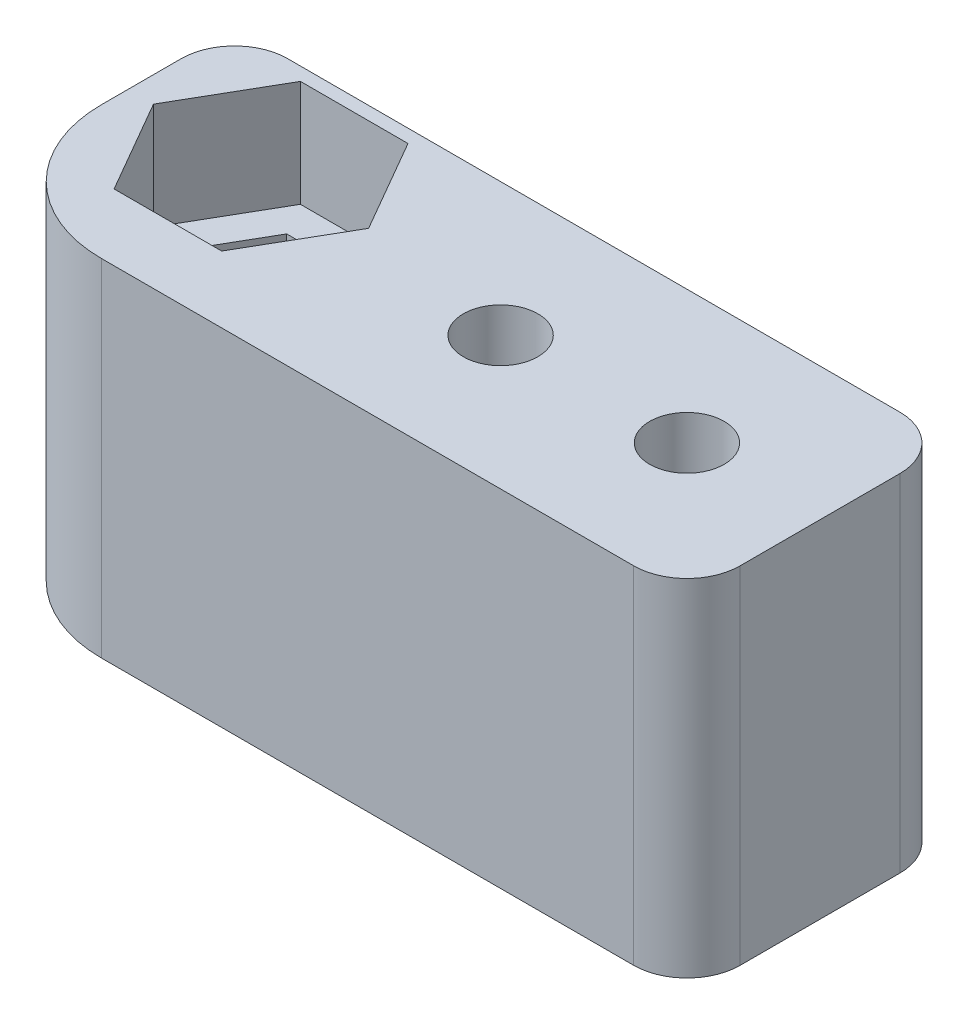
SolidWorks part; units mm, degrees
ref_plane "Front Plane" through (0, 0, 0) normal (0, 0, 1) x (1, 0, 0)
ref_plane "Top Plane" through (0, 0, 0) normal (0, 1, 0) x (1, 0, 0)
ref_plane "Right Plane" through (0, 0, 0) normal (1, 0, 0) x (0, 0, -1)
sketch "Sketch1" plane through (0, 0, 0) normal (0, 1, 0) x (1, 0, 0)
  line L1 (-19.05, 6.35) -> (15.24, 6.35)
  line L2 (-19.05, 6.35) -> (-19.05, -6.35)
  line L3 (-19.05, -6.35) -> (15.24, -6.35)
  line L4 (15.24, 6.35) -> (15.24, -6.35)
  circle A0 centre (-12.7, 1.27) radius 2.286
  circle A1 centre (0, 0) radius 1.778
  circle A2 centre (8.89, 0) radius 1.778
  dimension "D7" = 4.572
  dimension "D8" = 3.556
  dimension "D1" = 8.89
  dimension "D2" = 5.08
  dimension "D3" = 12.7
  dimension "D4" = 6.35
  dimension "D5" = 12.7
  dimension "D6" = 6.35
  dimension "D9" = 6.35
extrude "Boss-Extrude1" add sketch "Sketch1" along normal blind 16.51
fillet "Fillet1" radius 2.54 3 edges at (-19.05, 8.255, -6.35) (15.24, 8.255, -6.35) (15.24, 8.255, 6.35)
fillet "Fillet2" radius 6.35 1 edges at (-19.05, 8.255, 6.35)
sketch "Sketch4" plane through (0, 16.51, 0) normal (0, 1, 0) x (1, 0, 0)
  line L1 (-7.5674, 1.27) -> (-10.1337, 5.715)
  line L2 (-10.1337, 5.715) -> (-15.2663, 5.715)
  line L3 (-15.2663, 5.715) -> (-17.8326, 1.27)
  line L4 (-17.8326, 1.27) -> (-15.2663, -3.175)
  line L5 (-15.2663, -3.175) -> (-10.1337, -3.175)
  line L6 (-10.1337, -3.175) -> (-7.5674, 1.27)
  circle A0 centre (-12.7, 1.27) radius 4.445 construction
  dimension "D1" = 8.89
extrude "Cut-Extrude2" cut sketch "Sketch4" against normal blind 5.08
sketch "Sketch5" plane through (0, 11.43, 0) normal (0, 1, 0) x (1, 0, 0)
  line L1 (-9.3564, 1.27) -> (-11.0282, 4.1656)
  line L2 (-11.0282, 4.1656) -> (-14.3718, 4.1656)
  line L3 (-14.3718, 4.1656) -> (-16.0436, 1.27)
  line L4 (-16.0436, 1.27) -> (-14.3718, -1.6256)
  line L5 (-14.3718, -1.6256) -> (-11.0282, -1.6256)
  line L6 (-11.0282, -1.6256) -> (-9.3564, 1.27)
  circle A0 centre (-12.7, 1.27) radius 2.8956 construction
extrude "Cut-Extrude3" cut sketch "Sketch5" against normal offset from surface (8.89 mm away) 2.54 up to face at (-1.5274, 0, -0.3776)
